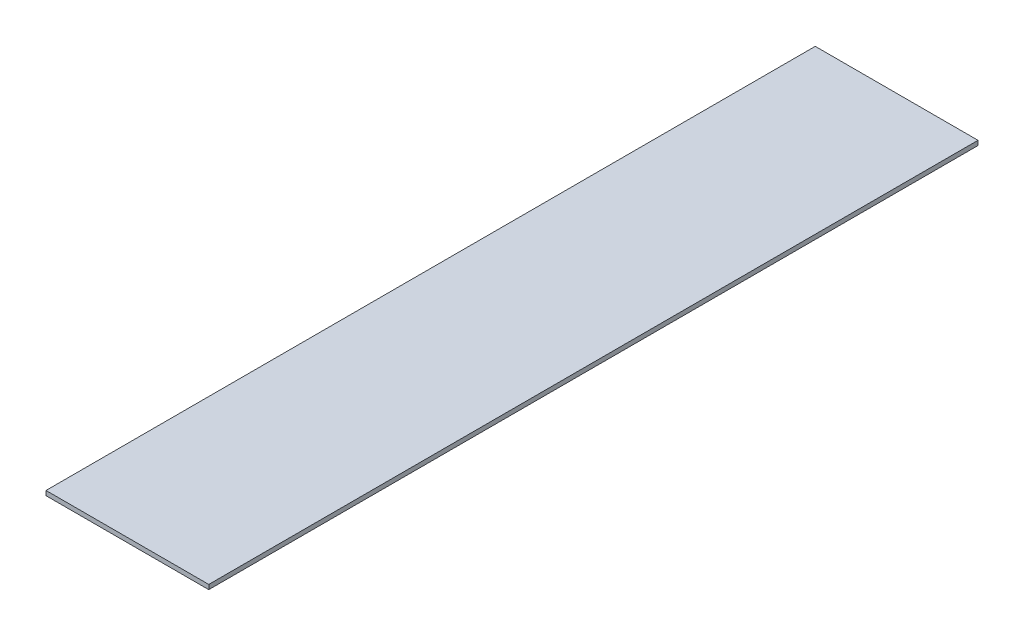
SolidWorks part; units mm, degrees
material "Thornel Mat VMA"
ref_plane "Front Plane" through (0, 0, 0) normal (0, 0, 1) x (1, 0, 0)
ref_plane "Top Plane" through (0, 0, 0) normal (0, 1, 0) x (1, 0, 0)
ref_plane "Right Plane" through (0, 0, 0) normal (1, 0, 0) x (0, 0, -1)
sketch "Sketch1" plane through (0, 0, 0) normal (0, 0, 1) x (1, 0, 0)
  line L1 (-22.375, 0.625) -> (22.375, 0.625)
  line L2 (-22.375, 0.625) -> (-22.375, -0.625)
  line L3 (-22.375, -0.625) -> (22.375, -0.625)
  line L4 (22.375, 0.625) -> (22.375, -0.625)
  line L5 (-22.375, 0.625) -> (22.375, -0.625) construction
  line L6 (-22.375, -0.625) -> (22.375, 0.625) construction
  point P0 (0, 0)
  dimension "D1" = 1.25
  dimension "D2" = 44.75
extrude "Boss-Extrude1" add sketch "Sketch1" along normal blind 211.5 contours L1 L4 L3 L2
equation "\"211.5.000mm\"=2115"
